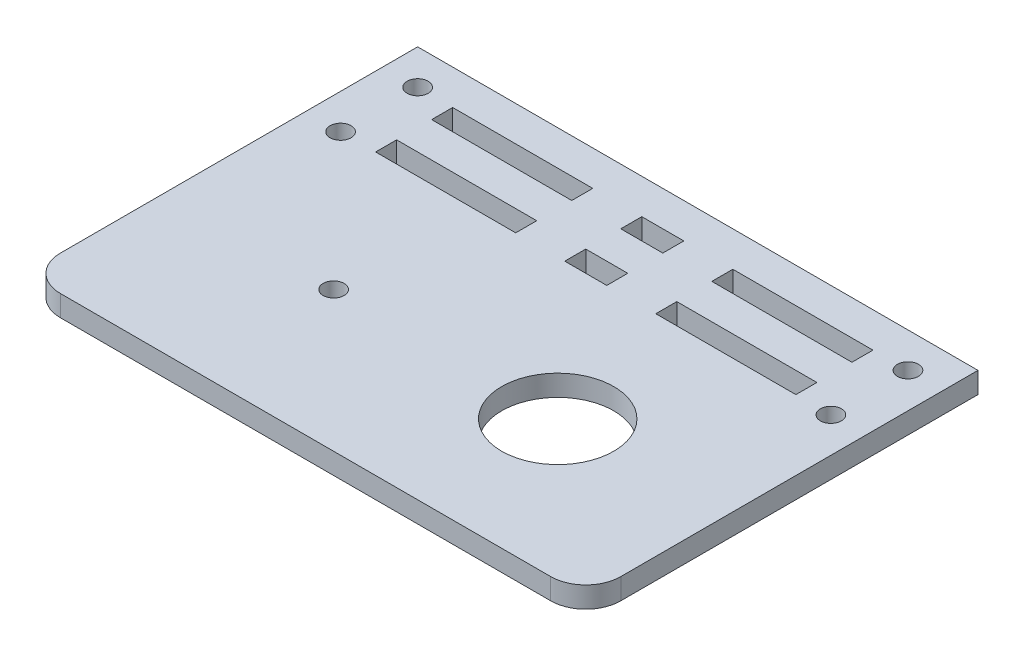
SolidWorks part; units mm, degrees
ref_plane "前视基准面" through (0, 0, 0) normal (0, 0, 1) x (1, 0, 0)
ref_plane "上视基准面" through (0, 0, 0) normal (0, 1, 0) x (1, 0, 0)
ref_plane "右视基准面" through (0, 0, 0) normal (1, 0, 0) x (0, 0, -1)
sketch "草图1" plane through (0, 0, 0) normal (0, 1, 0) x (1, 0, 0)
  line L0 (-30, 20) -> (-10, 20)
  line L8 (-40, 0) -> (-40, 20)
  line L10 (-40, 0) -> (-40, -15)
  line L11 (-35, -20) -> (0, -20)
  line L13 (0, -20) -> (35, -20)
  line L18 (-40, 20) -> (-40, 36)
  line L19 (-40, 36) -> (40, 36)
  line L20 (40, 20) -> (40, 36)
  line L22 (10, 23) -> (10, 20)
  line L23 (-20, 23) -> (-30, 23)
  line L24 (-30, 23) -> (-30, 20)
  line L25 (-20, 23) -> (-10, 23)
  line L26 (-10, 23) -> (-10, 20)
  line L27 (30, 23) -> (30, 20)
  line L28 (20, 23) -> (10, 23)
  line L29 (20, 23) -> (30, 23)
  line L30 (30, 28) -> (30, 31)
  line L31 (10, 28) -> (30, 28)
  line L32 (10, 31) -> (30, 31)
  line L33 (10, 28) -> (10, 31)
  line L34 (3, 28) -> (3, 31)
  line L35 (-10, 28) -> (-30, 28)
  line L36 (-10, 28) -> (-10, 31)
  line L37 (-10, 31) -> (-30, 31)
  line L38 (-30, 28) -> (-30, 31)
  line L40 (3, 28) -> (-3, 28)
  line L42 (3, 31) -> (-3, 31)
  line L43 (-3, 28) -> (-3, 31)
  line L44 (-3, 23) -> (-3, 20)
  line L45 (-3, 20) -> (3, 20)
  line L46 (3, 20) -> (3, 23)
  line L47 (3, 23) -> (-3, 23)
  line L48 (10, 20) -> (30, 20)
  line L49 (40, 20) -> (40, -15)
  line L50 (-40, 36) -> (-40, 31)
  circle A0 centre (16, 0) radius 8
  circle A1 centre (-16, 0) radius 1.5
  arc A2 (35, -20) -> (40, -15) centre (35, -15) ccw
  arc A3 (-40, -15) -> (-35, -20) centre (-35, -15) ccw
  circle A4 centre (-35, 31) radius 1.5
  circle A5 centre (-35, 20) radius 1.5
  circle A6 centre (35, 20) radius 1.5
  circle A7 centre (35, 31) radius 1.5
extrude "凸台-拉伸1" add sketch "草图1" along normal blind 3 contours L10 A3 L11 L13 A2 L49 L20 L19 L18 L8 A6 A5 A4 L40 L43 L42 L34 L35 L38 L37 L36 L31 L33 L32 L30 L25 L26 L0 L24 L23 L47 L46 L45 L44 L48 L22 L28 L29 L27 A0
